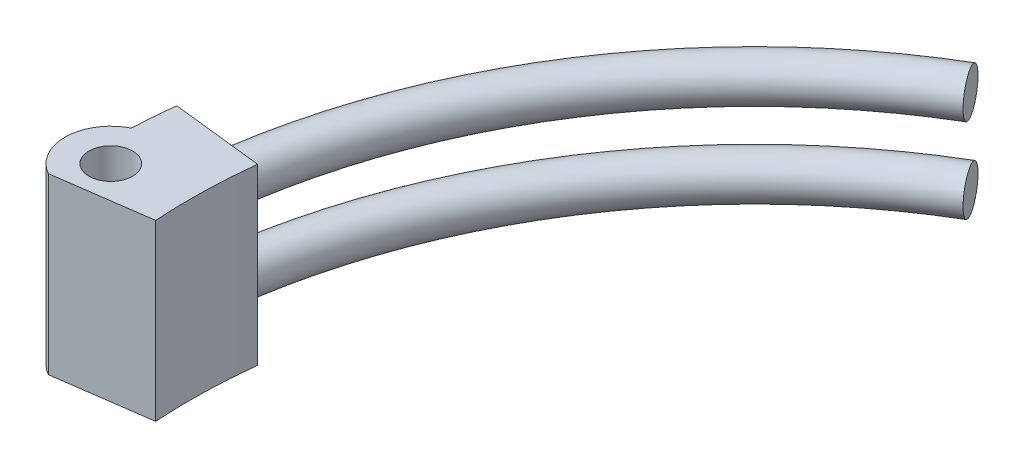
SolidWorks part; units mm, degrees
ref_plane "Front Plane" through (0, 0, 0) normal (0, 0, 1) x (1, 0, 0)
ref_plane "Top Plane" through (0, 0, 0) normal (0, 1, 0) x (1, 0, 0)
ref_plane "Right Plane" through (0, 0, 0) normal (1, 0, 0) x (0, 0, -1)
sketch "Sketch2" plane through (0, 0, 0) normal (0, 1, 0) x (1, 0, 0)
  line L0 (15, 0) -> (15, 84.2602) construction
  line L1 (-15, 0) -> (15, 0) construction
  line L2 (-15, 37.081) -> (-15, 44.0142)
  line L3 (-39.6131, -5.5501) -> (-46.0502, -6.452) construction
  line L4 (-15, 0) -> (-15, 85.092) construction
  line L5 (-15, 37.081) -> (15, 37.081) construction
  line L6 (39.6131, -5.5501) -> (24.6131, -31.5309) construction
  line L7 (-24.6131, -31.5309) -> (-39.6131, -5.5501) construction
  line L8 (0, 0) -> (-39.6131, -5.5501) construction
  line L9 (-46.2053, 5.2271) -> (-39.7465, 4.4964)
  line L10 (-40.0293, -2.5791) -> (-46.4665, -3.481)
  line L11 (-40.0293, -2.5791) -> (-39.9178, -2.5635)
  line L12 (-40.3068, -0.5985) -> (-39.6131, -5.5501) construction
  line L13 (-46.4665, -3.481) -> (-46.5916, -3.4986)
  line L14 (-40.3068, -0.5985) -> (0, 0) construction
  arc A2 (-39.6131, -5.5501) -> (-15, 37.081) centre (0, 0) cw
  arc A3 (-15, 44.0142) -> (-46.0502, -6.452) centre (0, 0) ccw
  circle A5 centre (0, 0) radius 50 construction
  circle A6 centre (-44.9945, -0.6681) radius 3.25
  circle A7 centre (-44.9945, -0.6681) radius 1.55
  point P10 (0, 0)
  point P31 (-49.9945, -0.7423)
  dimension "D1" = 46.5
  dimension "D2" = 40
  dimension "D4" = 100
  dimension "D10" = 6.5
  dimension "D11" = 3.1
  dimension "D3" = 3
  dimension "D6" = 14.43
  dimension "D7" = 5
  dimension "D8" = 5
  dimension "D9" = 30
  dimension "D5" = 3
extrude "Boss-Extrude1" add sketch "Sketch2" along normal blind 12.35
sketch "Sketch3" plane through (0, 0, 0) normal (0.1124, 0, -0.9937) x (-0.9937, 0, -0.1124)
  line L0 (43.4, 9.175) -> (43.4, 3.175) construction
  line L1 (43.4, 6.175) -> (40, 6.175) construction
  line L2 (40, 12.35) -> (40, 0) construction
  line L3 (46.5, 12.35) -> (40, 12.35) construction
  line L4 (46.5, 0) -> (40, 0) construction
  circle A0 centre (43.4, 9.175) radius 1.5
  circle A1 centre (43.4, 3.175) radius 1.5
  dimension "D1" = 3
  dimension "D2" = 3
  dimension "D3" = 6
  dimension "D4" = 3.4
sketch "Sketch7" plane through (0, 0, 0) normal (0, 1, 0) x (1, 0, 0)
  line L0 (0, 0) -> (-39.7465, 4.4964) construction
  line L1 (0, 0) -> (-20.329, 34.449) construction
  arc A0 (-39.7465, 4.4964) -> (-39.9178, -2.5635) centre (0, 0) ccw construction
  arc A1 (-39.7465, 4.4964) -> (-39.9178, -2.5635) centre (0, 0) ccw construction
  arc A3 (-39.7465, 4.4964) -> (-20.329, 34.449) centre (0, 0) cw
  dimension "D1" = 40
  dimension "D2" = 53
sweep "Sweep1" add profiles "Sketch3" path "Sketch7"
